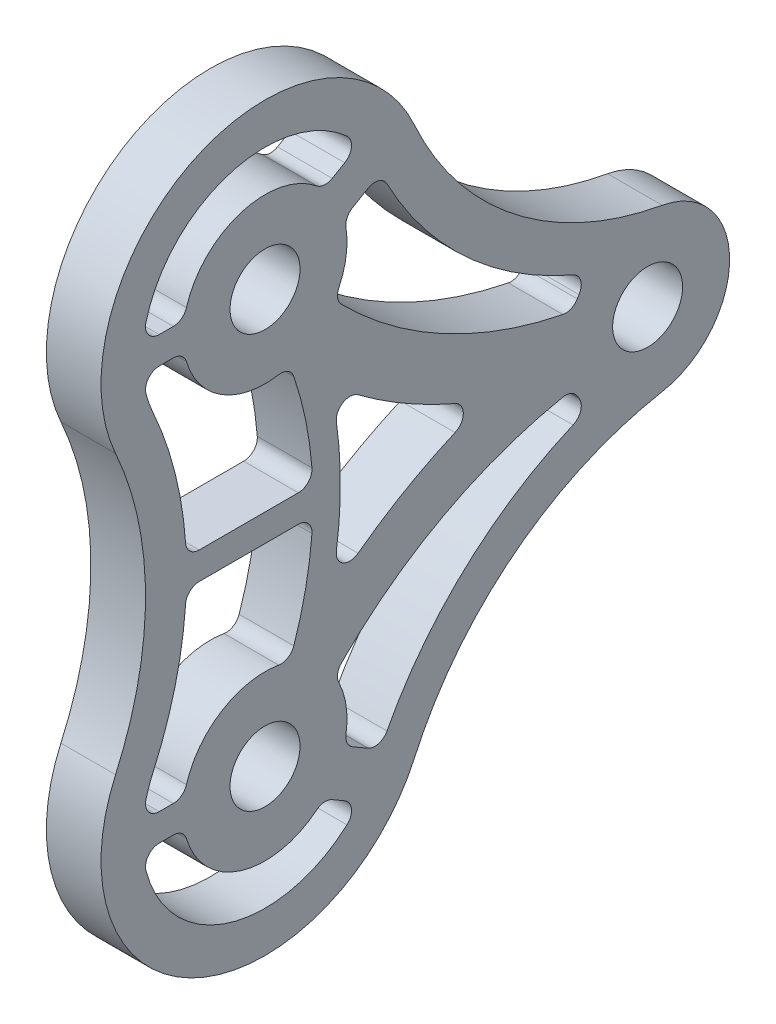
SolidWorks part; units mm, degrees
material "6061 Alloy"
ref_plane "Front Plane" through (0, 0, 0) normal (0, 0, 1) x (1, 0, 0)
ref_plane "Top Plane" through (0, 0, 0) normal (0, 1, 0) x (1, 0, 0)
ref_plane "Right Plane" through (0, 0, 0) normal (1, 0, 0) x (0, 0, -1)
sketch "Sketch1" plane through (0, 0, 0) normal (1, 0, 0) x (0, 0, -1)
  line L0 (-8.6806, -3.9208) -> (8.6806, 3.9208) construction
  arc A0 (8.6806, 3.9208) -> (-8.6806, -3.9208) centre (0, 0) ccw
  arc A1 (-8.6806, -20.0792) -> (8.6806, -27.9208) centre (0, -24) ccw
  arc A2 (-8.6806, -3.9208) -> (-8.6806, -20.0792) centre (-26.5679, -12) cw
  arc A3 (23.073, -7.3136) -> (23.073, -16.6864) centre (22.225, -12) cw
  arc A4 (23.073, -16.6864) -> (8.6806, -27.9208) centre (26.5679, -36) ccw
  arc A5 (23.073, -7.3136) -> (8.6806, 3.9208) centre (26.5679, 12) cw
  circle A6 centre (0, 0) radius 2.032
  circle A7 centre (0, -24) radius 2.032
  circle A8 centre (22.225, -12) radius 2.032
  dimension "D1" = 24
  dimension "D2" = 19.05
  dimension "D3" = 4.7625
  dimension "D5" = 4.064
  dimension "D6" = 4.064
  dimension "D4" = 22.225
extrude "Boss-Extrude1" add sketch "Sketch1" along normal blind 3.175
sketch "Sketch3" plane through (3.175, 0, 0) normal (1, 0, 0) x (0, 0, -1)
  line L0 (2.7764, -12.7938) -> (-4.5737, -12.7938)
  line L2 (-4.5737, -11.2062) -> (2.7764, -11.2062)
  line L3 (-7.0995, -23.2063) -> (-4.6959, -23.2063)
  line L6 (-4.6959, -24.7937) -> (-7.0995, -24.7938)
  line L12 (0, -24) -> (3.9935, -26.3056) construction
  line L15 (0, -24) -> (0, 0) construction
  line L16 (3.3982, -27.3367) -> (5.5048, -28.553)
  line L19 (4.5888, -25.2745) -> (6.7145, -26.5018)
  line L21 (3.3982, -27.3367) -> (4.5888, -25.2745) construction
  line L23 (22.225, -12) -> (-6.9407, -12) construction
  line L25 (4.5888, 1.2745) -> (6.7145, 2.5018)
  line L26 (3.3982, 3.3367) -> (5.5048, 4.553)
  line L27 (-7.0995, -0.7938) -> (-4.6959, -0.7937)
  line L28 (-4.6959, 0.7937) -> (-7.0995, 0.7937)
  arc A55 (4.5888, -25.2745) -> (4.0237, -21.4523) centre (0, -24) ccw
  arc A64 (-8.6806, -20.0792) -> (-8.6806, -3.9208) centre (-26.5679, -12) ccw construction
  arc A66 (3.3982, 3.3367) -> (-4.6959, 0.7937) centre (0, 0) ccw
  arc A67 (-4.6959, -0.7937) -> (1.4285, -4.5432) centre (0, 0) ccw
  arc A68 (-7.0995, -0.7938) -> (-6.5105, -2.9406) centre (0, 0) ccw
  arc A93 (4.0237, -2.5477) -> (4.5888, 1.2745) centre (0, 0) ccw
  arc A94 (1.4285, -19.4568) -> (-4.6959, -23.2063) centre (0, -24) ccw
  arc A95 (18.8711, -8.6188) -> (17.8876, -10.0333) centre (22.225, -12) ccw
  arc A96 (23.073, -16.6864) -> (23.073, -7.3136) centre (22.225, -12) ccw construction
  arc A97 (22.225, -12) -> (0, 0) centre (22.225, 14.5813) cw construction
  arc A98 (0, 0) -> (0, -24) centre (-18.2906, -12) cw construction
  arc A109 (-6.5105, -21.0594) -> (-6.5105, -2.9406) centre (-26.5679, -12) ccw
  arc A110 (-6.5105, -21.0594) -> (6.5105, -26.9406) centre (0, -24) ccw
  arc A111 (22.649, -14.3432) -> (6.5105, -26.9406) centre (26.5679, -36) ccw
  arc A112 (22.649, -14.3432) -> (22.649, -9.6568) centre (22.225, -12) ccw
  arc A113 (6.5105, 2.9406) -> (22.649, -9.6568) centre (26.5679, 12) ccw
  arc A114 (6.5105, 2.9406) -> (-6.5105, -2.9406) centre (0, 0) ccw
  arc A115 (-6.5105, -21.0594) -> (-4.5737, -12.7938) centre (-26.5679, -12) ccw
  arc A116 (-6.5105, -21.0594) -> (-7.0995, -23.2063) centre (0, -24) ccw
  arc A117 (18.8711, -15.3812) -> (6.7145, -26.5018) centre (26.5679, -36) ccw
  arc A119 (6.7145, 2.5018) -> (18.8711, -8.6188) centre (26.5679, 12) ccw
  arc A120 (5.5048, 4.553) -> (-7.0995, 0.7937) centre (0, 0) ccw
  arc A121 (0, -24) -> (22.225, -12) centre (22.225, -38.5813) cw construction
  arc A122 (17.8876, -10.0333) -> (4.0237, -2.5477) centre (22.225, 14.5813) cw
  arc A123 (12.9021, -12) -> (3.7455, -6.6787) centre (22.225, 14.5813) cw
  arc A124 (4.0237, -21.4523) -> (17.8876, -13.9667) centre (22.225, -38.5813) cw
  arc A126 (1.4285, -4.5432) -> (2.7764, -11.2062) centre (-18.2906, -12) cw
  arc A127 (2.7764, -12.7938) -> (1.4285, -19.4568) centre (-18.2906, -12) cw
  arc A128 (22.225, -10.4125) -> (1.3273, 0.8708) centre (22.225, 14.5813) cw construction
  arc A129 (1.3273, -24.8708) -> (22.225, -13.5875) centre (22.225, -38.5813) cw construction
  arc A130 (22.225, -13.5875) -> (-1.3273, -0.8708) centre (22.225, 14.5813) cw construction
  arc A131 (-0.6637, -0.4354) -> (-0.6637, -23.5646) centre (-18.2906, -12) cw construction
  arc A132 (3.7455, -6.6787) -> (3.7455, -17.3213) centre (-18.2906, -12) cw
  arc A133 (-4.5737, -11.2062) -> (-6.5105, -2.9406) centre (-26.5679, -12) ccw
  arc A134 (17.8876, -13.9667) -> (18.8711, -15.3812) centre (22.225, -12) ccw
  arc A135 (3.7455, -17.3213) -> (12.9021, -12) centre (22.225, -38.5813) cw
  arc A136 (-4.6959, -24.7937) -> (3.3982, -27.3367) centre (0, -24) ccw
  arc A137 (-7.0995, -24.7938) -> (5.5048, -28.553) centre (0, -24) ccw
  point P56 (3.9935, -26.3056)
  dimension "D2" = 9.525
  dimension "D6" = 1.5875
  dimension "D8" = 0.7937
  dimension "D3" = 1.5875
  dimension "D7" = 0.7937
  dimension "D1" = 2.3813
  dimension "D5" = 1.5875
  dimension "D4" = 1.5875
  dimension "D9" = 1.5875
  dimension "D10" = 1.5875
  dimension "D11" = 120
  dimension "D12" = 2.3813
extrude "Cut-Extrude3" cut sketch "Sketch3" against normal through all
fillet "Fillet7" radius 0.7937 31 edges at (1.5875, -15.3812, -18.8711) (1.5875, -27.3367, -3.3982) (1.5875, -28.553, -5.5048) (1.5875, -26.5018, -6.7145) (1.5875, -21.4523, -4.0237) (1.5875, -25.2745, -4.5888) (1.5875, -24.7937, 4.6959) (1.5875, -24.7938, 7.0995) (1.5875, -23.2063, 7.0995) (1.5875, -23.2063, 4.6959) (1.5875, -19.4568, -1.4285) (1.5875, -12.7938, -2.7764) (1.5875, -12.7938, 4.5737) (1.5875, -11.2062, 4.5737) (1.5875, -11.2062, -2.7764) (1.5875, 4.553, -5.5048) (1.5875, 3.3367, -3.3982) (1.5875, 0.7937, 4.6959) (1.5875, 0.7937, 7.0995) (1.5875, -0.7938, 7.0995) (1.5875, -0.7937, 4.6959) (1.5875, -4.5432, -1.4285) (1.5875, -2.5477, -4.0237) (1.5875, 1.2745, -4.5888) (1.5875, 2.5018, -6.7145) (1.5875, -13.9667, -17.8876) (1.5875, -17.3213, -3.7455) (1.5875, -6.6787, -3.7455) (1.5875, -12, -12.9021) (1.5875, -10.0333, -17.8876) (1.5875, -8.6188, -18.8711)
